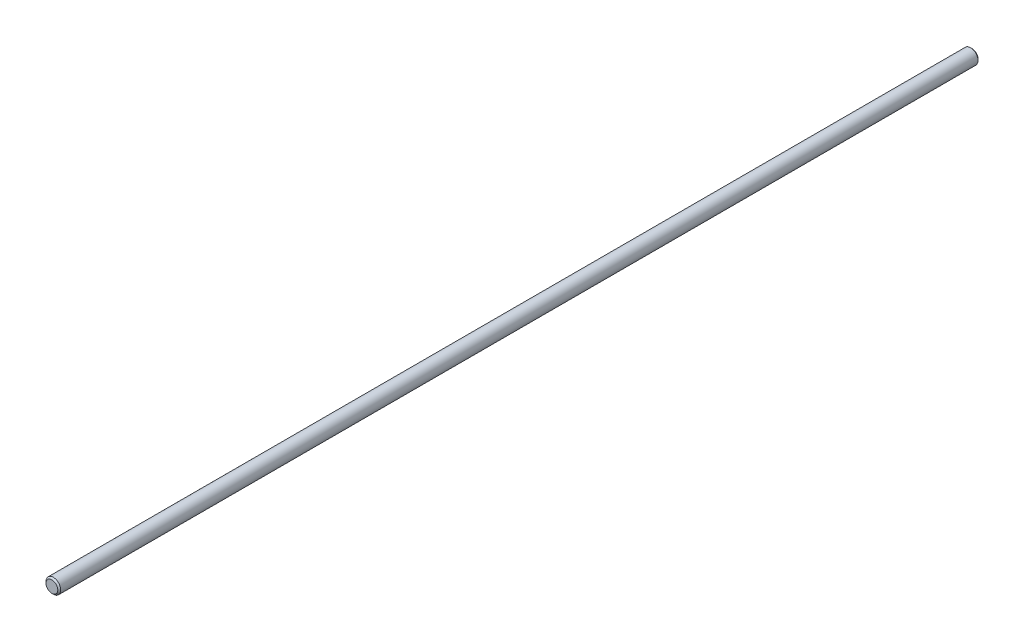
SolidWorks part; units mm, degrees
ref_plane "Front" through (0, 0, 0) normal (0, 0, 1) x (1, 0, 0)
ref_plane "Top" through (0, 0, 0) normal (0, 1, 0) x (1, 0, 0)
ref_plane "Right" through (0, 0, 0) normal (1, 0, 0) x (0, 0, -1)
sketch "Sketch1" plane through (0, 0, 0) normal (0, 0, 1) x (1, 0, 0)
  circle A0 centre (0, 0) radius 4
  dimension "dia" = 8
extrude "Extrude1" add sketch "Sketch1" along normal mid plane 500
sketch "Sketch2" plane through (0, 0, 0) normal (1, 0, 0) x (0, 0, -1)
  point P0 (-250, 4)
  point P1 (250, 4)
chamfer "Chamfer1" distance 0.8 angle 45 2 edges at (4, 0, -250) (4, 0, 250)
equation "\"D1@Chamfer1\" = \"dia@Sketch1\" * .1"
